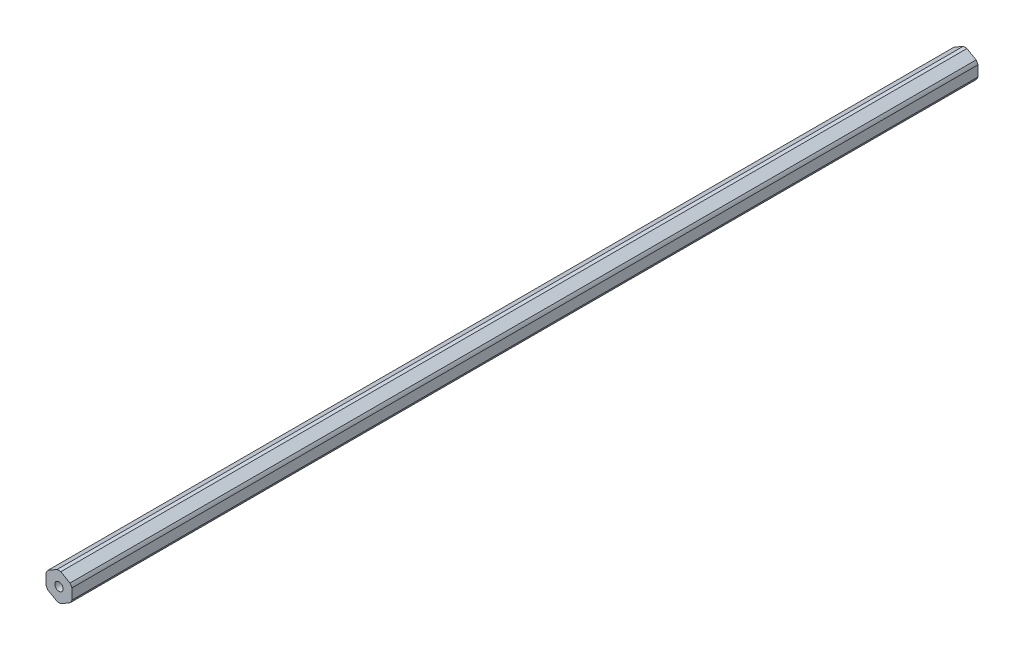
SolidWorks part; units mm, degrees
ref_plane "Front Plane" through (0, 0, 0) normal (0, 0, 1) x (1, 0, 0)
ref_plane "Top Plane" through (0, 0, 0) normal (0, 1, 0) x (1, 0, 0)
ref_plane "Right Plane" through (0, 0, 0) normal (1, 0, 0) x (0, 0, -1)
sketch "Sketch1" plane through (0, 0, 0) normal (0, 0, 1) x (1, 0, 0)
  line L1 (6.35, 3.6662) -> (0, 7.3323)
  line L2 (0, 7.3323) -> (-6.35, 3.6662)
  line L3 (-6.35, 3.6662) -> (-6.35, -3.6662)
  line L4 (-6.35, -3.6662) -> (0, -7.3323)
  line L5 (0, -7.3323) -> (6.35, -3.6662)
  line L6 (6.35, -3.6662) -> (6.35, 3.6662)
  circle A0 centre (0, 0) radius 6.35 construction
  circle A1 centre (0, 0) radius 6.858
  dimension "D1" = 12.7
  dimension "D2" = 13.716
extrude "Boss-Extrude1" add sketch "Sketch1" along normal blind 444.5 contours L6 A1 L1 L2 L3 L4 L5
hole_wizard "#10-32 Tapped Hole1" positions "3DSketch1" profile "Sketch2" tap size "#10-32" standard "ANSI Inch"
sketch3d "3DSketch1"
  line L0 (0, 0, 444.5) -> (0, 0, 0) construction
  arc A3 (0.9317, 6.7944, 0) -> (-0.9317, 6.7944, 0) centre (0, 0, 0) ccw construction
  point P0 (0, 0, 444.5)
  point P7 (0, 0, 0)
  point P10 (0, 0, 0)
  point P12 (0, 0, 0)
  point P14 (0, 0, 0)
  point P17 (0, 0, 0)
  point P18 (-12.0153, -11.3492, 0)
  point P31 (-0.9995, -1.7312, 0)
  point P35 (0, 0, 6.858)
sketch "Sketch2" plane through (0, 0, 444.5) normal (1, 0, 0) x (0, -1, 0)
  line L0 (0, 0) -> (0, 16.2908)
  line L1 (0, 16.2908) -> (2.0193, 15.0774)
  line L2 (2.0193, 15.0774) -> (2.0193, 0)
  line L5 (2.0193, 0) -> (0, 0)
  line L10 (0, 16.2908) -> (-2.0193, 15.0774) construction
  line L11 (0, -6.35) -> (0, 107.95) construction
  dimension "Tap Drill Dia." = 4.0386
  dimension "Tap Drill Depth" = 15.0774
  dimension "Drill Angle" = 118
cosmetic thread "Hole Thread1" parameters "D1"=12.7, "D2"=4.826
cosmetic thread "Hole Thread2" parameters "D1"=12.7, "D2"=4.826
cosmetic thread "Hole Thread3" parameters "D1"=12.7, "D2"=4.826
cosmetic thread "Hole Thread4" parameters "D1"=12.7, "D2"=4.826
cosmetic thread "Hole Thread5" parameters "D1"=12.7, "D2"=4.826
